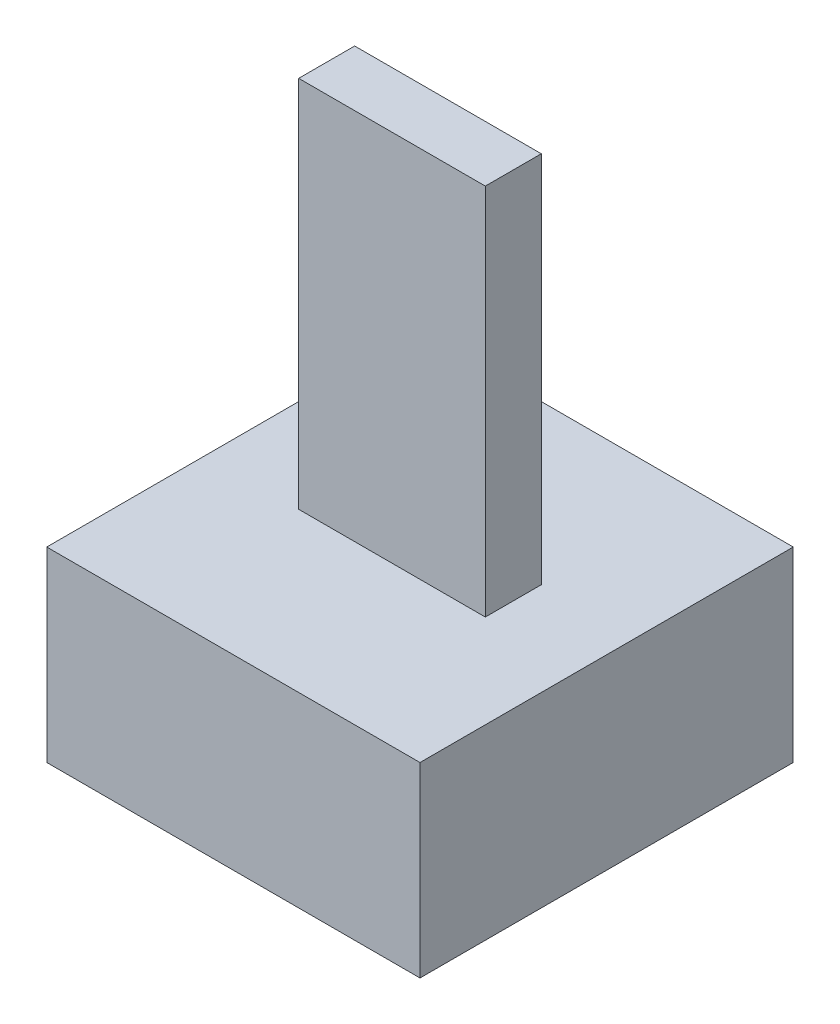
SolidWorks part; units mm, degrees
ref_plane "前视基准面" through (0, 0, 0) normal (0, 0, 1) x (1, 0, 0)
ref_plane "上视基准面" through (0, 0, 0) normal (0, 1, 0) x (1, 0, 0)
ref_plane "右视基准面" through (0, 0, 0) normal (1, 0, 0) x (0, 0, -1)
other "Configuration Table"
sketch "草图1" plane through (0, 0, 0) normal (0, 1, 0) x (1, 0, 0)
  line L1 (-5, 5) -> (5, 5)
  line L2 (-5, 5) -> (-5, -5)
  line L3 (-5, -5) -> (5, -5)
  line L4 (5, 5) -> (5, -5)
  line L5 (-5, 5) -> (5, -5) construction
  line L6 (-5, -5) -> (5, 5) construction
  point P0 (0, 0)
  dimension "D1" = 10
  dimension "D2" = 10
extrude "凸台-拉伸1" add sketch "草图1" along normal blind 5
sketch "草图2" plane through (0, 5, 0) normal (0, 1, 0) x (1, 0, 0)
  line L1 (-2.5, 0.75) -> (2.5, 0.75)
  line L2 (-2.5, 0.75) -> (-2.5, -0.75)
  line L3 (-2.5, -0.75) -> (2.5, -0.75)
  line L4 (2.5, 0.75) -> (2.5, -0.75)
  line L5 (-2.5, 0.75) -> (2.5, -0.75) construction
  line L6 (-2.5, -0.75) -> (2.5, 0.75) construction
  point P0 (0, 0)
  dimension "D1" = 1.5
  dimension "D2" = 5
extrude "凸台-拉伸2" add sketch "草图2" along normal blind 10
